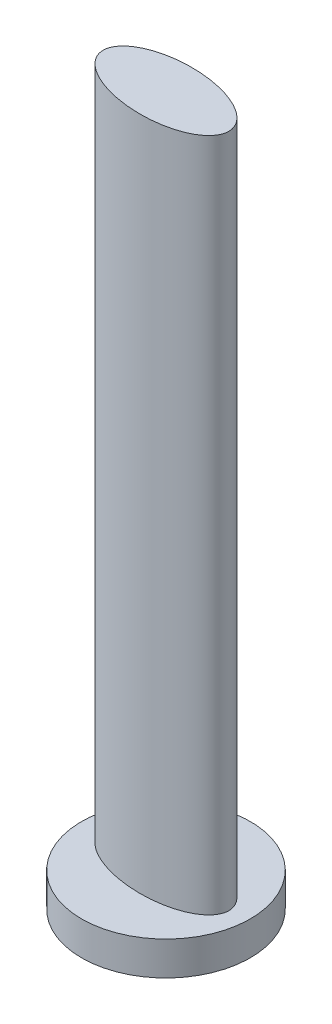
SolidWorks part; units mm, degrees
ref_plane "Front Plane" through (0, 0, 0) normal (0, 0, 1) x (1, 0, 0)
ref_plane "Top Plane" through (0, 0, 0) normal (0, 1, 0) x (1, 0, 0)
ref_plane "Right Plane" through (0, 0, 0) normal (1, 0, 0) x (0, 0, -1)
sketch "Sketch6" plane through (0, 0, 0) normal (0, 1, 0) x (1, 0, 0)
  circle A0 centre (0, 0) radius 10
  dimension "D1" = 20
extrude "Boss-Extrude3" add sketch "Sketch6" along normal blind 4
sketch "Sketch7" plane through (0, 4, 0) normal (0, 1, 0) x (1, 0, 0)
  ellipse E0 centre (0, 0) end of major axis (-7.879, 0.575) minor radius 3.9
  dimension "D1" = 7.9
  dimension "D2" = 3.9
extrude "Boss-Extrude4" add sketch "Sketch7" along normal blind 80
